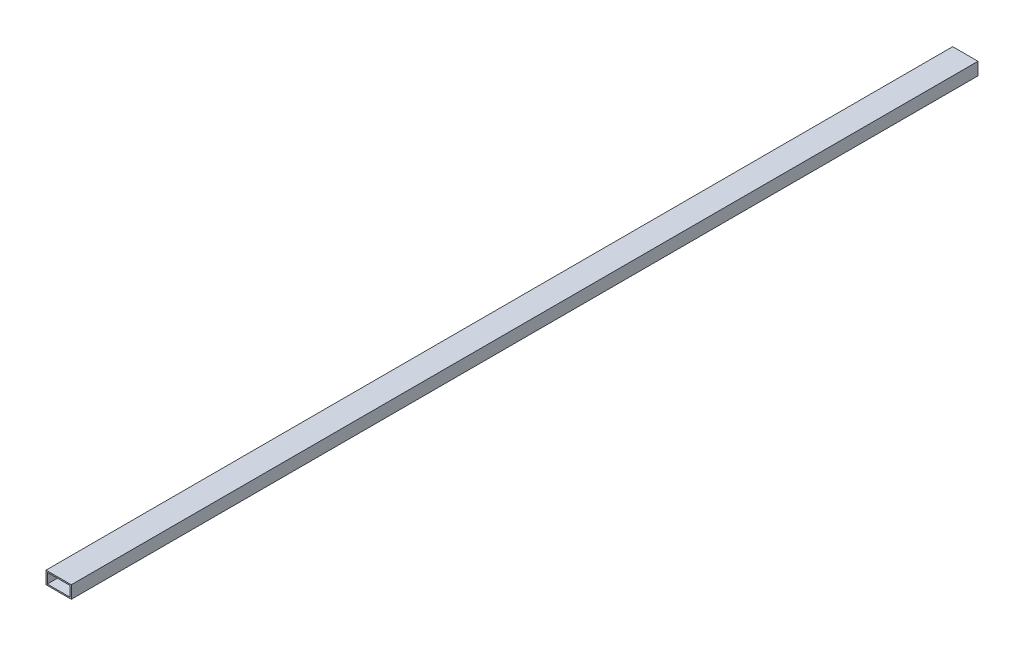
SolidWorks part; units mm, degrees
material "2024-O"
ref_plane "Alzado" through (0, 0, 0) normal (0, 0, 1) x (1, 0, 0)
ref_plane "Planta" through (0, 0, 0) normal (0, 1, 0) x (1, 0, 0)
ref_plane "Vista lateral" through (0, 0, 0) normal (1, 0, 0) x (0, 0, -1)
sketch "Croquis1" plane through (0, 0, 0) normal (0, 0, 1) x (1, 0, 0)
  line L1 (20, -10) -> (-20, -10)
  line L2 (20, -10) -> (20, 10)
  line L3 (20, 10) -> (-20, 10)
  line L4 (-20, -10) -> (-20, 10)
  line L5 (20, -10) -> (-20, 10) construction
  line L6 (20, 10) -> (-20, -10) construction
  point P0 (0, 0)
  dimension "D1" = 40
  dimension "D2" = 20
extrude "Extruir-Lámina1" add sketch "Croquis1" along normal blind 1433 thin
